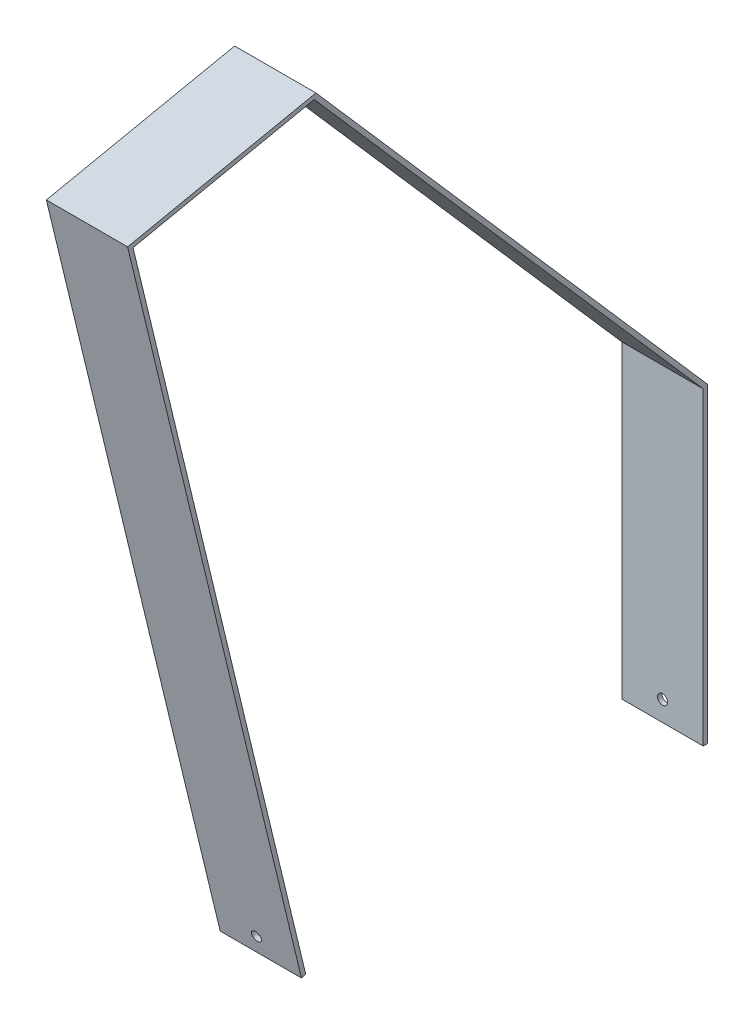
SolidWorks part; units mm, degrees
ref_plane "Front Plane" through (0, 0, 0) normal (0, 0, 1) x (1, 0, 0)
ref_plane "Top Plane" through (0, 0, 0) normal (0, 1, 0) x (1, 0, 0)
ref_plane "Right Plane" through (0, 0, 0) normal (1, 0, 0) x (0, 0, -1)
sketch "Sketch4" plane through (117.5682, 0, 0) normal (-1, 0, 0) x (0, 0, 1)
  line L0 (-1238.3761, 78.04) -> (-692.4023, 78.04) construction
  line L1 (-1089.669, 78.04) -> (-1089.669, 264.04)
  line L2 (-1089.669, 264.04) -> (-855.4029, 532.0986)
  line L3 (-855.4029, 532.0986) -> (-742.8136, 508.6752)
  line L4 (-742.8136, 508.6752) -> (-846.7479, 78.04)
  line L5 (-1087.009, 78.04) -> (-1087.009, 263.0415)
  line L6 (-1087.009, 263.0415) -> (-854.4229, 529.1777)
  line L7 (-854.4229, 529.1777) -> (-746.0436, 506.6302)
  line L8 (-746.0436, 506.6302) -> (-849.3336, 78.6641)
  line L9 (-1089.669, 78.04) -> (-1087.009, 78.04)
  line L10 (-849.3336, 78.6641) -> (-846.7479, 78.04)
  line L14 (-852.3951, 65.9794) -> (-841.6322, 110.5738) construction
  line L17 (-1089.669, 87.0409) -> (-1089.669, 93.0409) construction
  arc A0 (-1040.7028, 273.0765) -> (-837.0704, 172.5339) centre (-952.329, 195.58) ccw construction
  arc A2 (-865.2035, 54.3409) -> (-854.3971, 73.7126) centre (-865.2035, 67.0409) ccw construction
  dimension "D2" = 115
  dimension "D3" = 356
  dimension "D4" = 186
  dimension "D5" = 443
  dimension "D6" = 88.183
  dimension "D1" = 2.66
extrude "Boss-Extrude2" add sketch "Sketch4" along normal mid plane 48.6
sketch "Sketch5" plane through (0, 0, -1089.669) normal (0, 0, -1) x (-1, 0, 0)
  circle A0 centre (-117.5682, 90.0409) radius 3
extrude "Cut-Extrude1" cut sketch "Sketch5" against normal blind 10
sketch "Sketch10" plane through (0, 198.0342, -820.5235) normal (0, 0.2346, -0.9721) x (-1, 0, 0)
  circle A0 centre (-117.5682, -111.8196) radius 3
  dimension "D1" = 6
extrude "Cut-Extrude2" cut sketch "Sketch10" against normal blind 10
